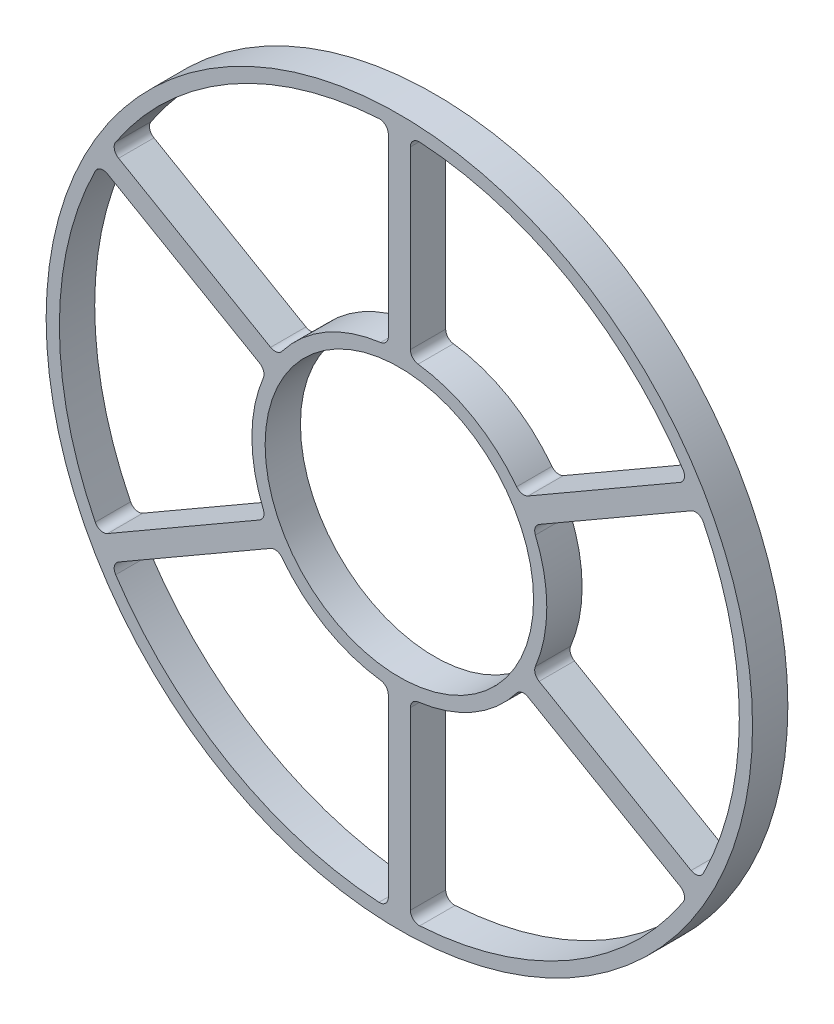
SolidWorks part; units mm, degrees
ref_plane "Front Plane" through (0, 0, 0) normal (0, 0, 1) x (1, 0, 0)
ref_plane "Top Plane" through (0, 0, 0) normal (0, 1, 0) x (1, 0, 0)
ref_plane "Right Plane" through (0, 0, 0) normal (1, 0, 0) x (0, 0, -1)
sketch "Sketch1" plane through (0, 0, 0) normal (0, 0, 1) x (1, 0, 0)
  line L0 (-1.25, 16.6532) -> (-1.25, 38.4797)
  line L1 (1.25, 38.4797) -> (1.25, 16.6532)
  line L2 (33.9494, 18.1573) -> (15.0471, 7.244)
  line L3 (13.7971, 9.4091) -> (32.6994, 20.3224)
  line L4 (32.6994, -20.3224) -> (13.7971, -9.4091)
  line L5 (15.0471, -7.244) -> (33.9494, -18.1573)
  line L6 (-1.25, -38.4797) -> (-1.25, -16.6532)
  line L7 (1.25, -16.6532) -> (1.25, -38.4797)
  line L8 (-33.9494, -18.1573) -> (-15.0471, -7.244)
  line L9 (-13.7971, -9.4091) -> (-32.6994, -20.3224)
  line L10 (-32.6994, 20.3224) -> (-13.7971, 9.4091)
  line L11 (-15.0471, 7.244) -> (-33.9494, 18.1573)
  circle A0 centre (0, 0) radius 15.2
  arc A1 (-13.7971, -9.4091) -> (-1.25, -16.6532) centre (0, 0) ccw
  arc A2 (-33.9494, 18.1573) -> (-33.9494, -18.1573) centre (0, 0) ccw
  circle A4 centre (0, 0) radius 40
  circle A5 centre (0, 0) radius 38.5 construction
  arc A6 (-32.6994, -20.3224) -> (-1.25, -38.4797) centre (0, 0) ccw
  arc A7 (-15.0471, 7.244) -> (-15.0471, -7.244) centre (0, 0) ccw
  arc A8 (-1.25, 16.6532) -> (-13.7971, 9.4091) centre (0, 0) ccw
  arc A9 (-1.25, 38.4797) -> (-32.6994, 20.3224) centre (0, 0) ccw
  arc A10 (32.6994, 20.3224) -> (1.25, 38.4797) centre (0, 0) ccw
  arc A11 (13.7971, 9.4091) -> (1.25, 16.6532) centre (0, 0) ccw
  arc A12 (15.0471, -7.244) -> (15.0471, 7.244) centre (0, 0) ccw
  arc A13 (33.9494, -18.1573) -> (33.9494, 18.1573) centre (0, 0) ccw
  arc A14 (1.25, -16.6532) -> (13.7971, -9.4091) centre (0, 0) ccw
  arc A15 (1.25, -38.4797) -> (32.6994, -20.3224) centre (0, 0) ccw
  point P34 (0, 0)
  dimension "D1" = 30.4
  dimension "D2" = 1.5
  dimension "D3" = 1.5
  dimension "D4" = 80
  dimension "D5" = 2.5
  dimension "D6" = 6
extrude "Boss-Extrude1" add sketch "Sketch1" along normal mid plane 4 contours A4 A15 L7 A14 L4 A13 L5 A12 L2 A9 L0 A8 L10 A6 L9 A1 L6 A0 L11 A7 L8 A2 L3 A11 L1 A10
fillet "Fillet2" radius 1 24 edges at (-15.0471, -7.244, 0) (32.6994, 20.3224, 0) (1.25, 38.4797, 0) (1.25, 16.6532, 0) (13.7971, 9.4091, 0) (-33.9494, 18.1573, 0) (-33.9494, -18.1573, 0) (-15.0471, 7.244, 0) (-1.25, -38.4797, 0) (-1.25, -16.6532, 0) (-13.7971, -9.4091, 0) (-32.6994, -20.3224, 0) (-32.6994, 20.3224, 0) (-13.7971, 9.4091, 0) (-1.25, 16.6532, 0) (-1.25, 38.4797, 0) (33.9494, 18.1573, 0) (15.0471, 7.244, 0) (15.0471, -7.244, 0) (33.9494, -18.1573, 0) (32.6994, -20.3224, 0) (13.7971, -9.4091, 0) (1.25, -16.6532, 0) (1.25, -38.4797, 0)
